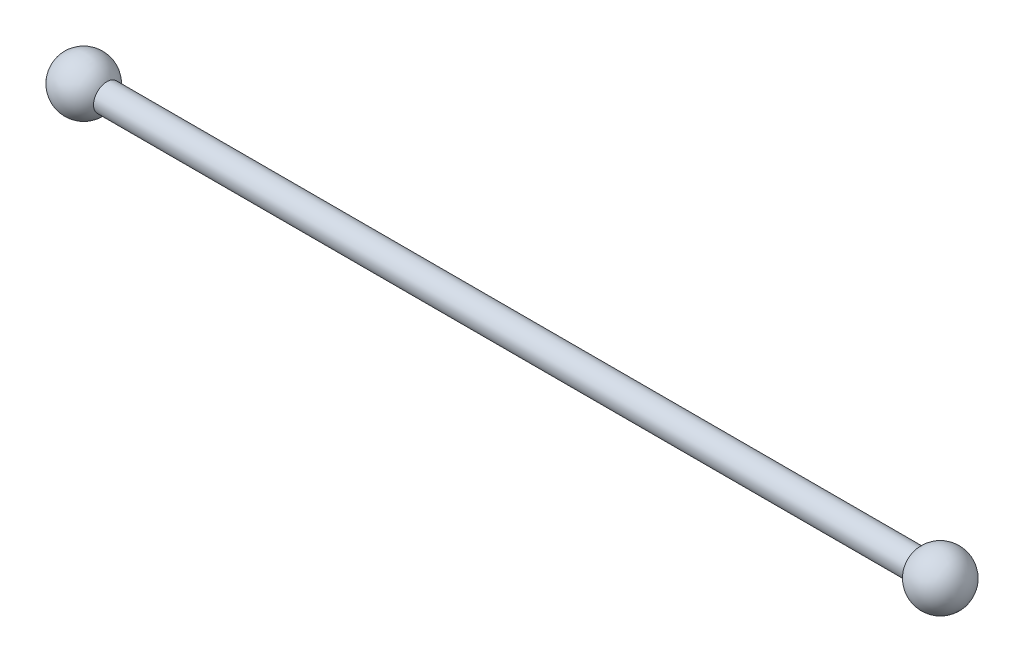
SolidWorks part; units mm, degrees
ref_plane "Front Plane" through (0, 0, 0) normal (0, 0, 1) x (1, 0, 0)
ref_plane "Top Plane" through (0, 0, 0) normal (0, 1, 0) x (1, 0, 0)
ref_plane "Right Plane" through (0, 0, 0) normal (1, 0, 0) x (0, 0, -1)
sketch "Sketch1" plane through (0, 0, 0) normal (0, 0, 1) x (1, 0, 0)
  line L0 (42.5, 0) -> (-42.5, 0)
  line L1 (0, 1.25) -> (0, 0) construction
  line L2 (0, 0) -> (-45.8846, 0) construction
  line L3 (37.8349, 1.25) -> (-37.8349, 1.25)
  arc A0 (37.8349, 1.25) -> (42.5, 0) centre (40, 0) cw
  arc A2 (-37.8349, 1.25) -> (-42.5, 0) centre (-40, 0) ccw
  point P0 (0, 0)
  dimension "D3" = 2.5
  dimension "D1" = 40
  dimension "D2" = 2.5
revolve "Revolve2" add sketch "Sketch1" angle 360 about L2
